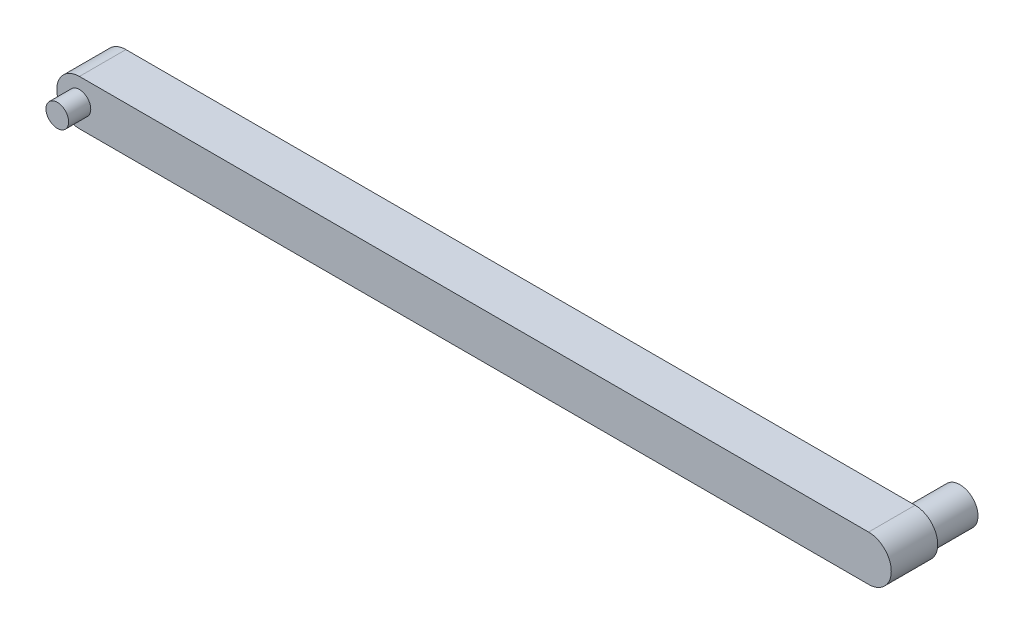
SolidWorks part; units mm, degrees
ref_plane "Plan de face" through (0, 0, 0) normal (0, 0, 1) x (1, 0, 0)
ref_plane "Plan de dessus" through (0, 0, 0) normal (0, 1, 0) x (1, 0, 0)
ref_plane "Plan de droite" through (0, 0, 0) normal (1, 0, 0) x (0, 0, -1)
sketch "Esquisse1" plane through (0, 0, 0) normal (0, 0, 1) x (1, 0, 0)
  line L1 (-28.7902, 6.6031) -> (145.2098, 6.6031)
  line L3 (-28.7902, -3.3969) -> (145.2098, -3.3969)
  arc A0 (-28.7902, 6.6031) -> (-28.7902, -3.3969) centre (-28.7902, 1.6031) ccw
  arc A1 (145.2098, -3.3969) -> (145.2098, 6.6031) centre (145.2098, 1.6031) ccw
  dimension "D2" = 10
  dimension "D3" = 10
  dimension "D1" = 10
extrude "Boss.-Extru.1" add sketch "Esquisse1" along normal mid plane 10.25
sketch "Esquisse2" plane through (0, 0, 0) normal (0, 0, 1) x (1, 0, 0)
  circle A0 centre (-28.7902, 1.6031) radius 2.5
  dimension "D1" = 5
extrude "Boss.-Extru.2" add sketch "Esquisse2" along normal blind 10
sketch "Esquisse3" plane through (0, 0, 0) normal (0, 0, 1) x (1, 0, 0)
  circle A0 centre (145.2098, 1.6031) radius 4
  dimension "D1" = 8
extrude "Boss.-Extru.3" add sketch "Esquisse3" against normal blind 15
